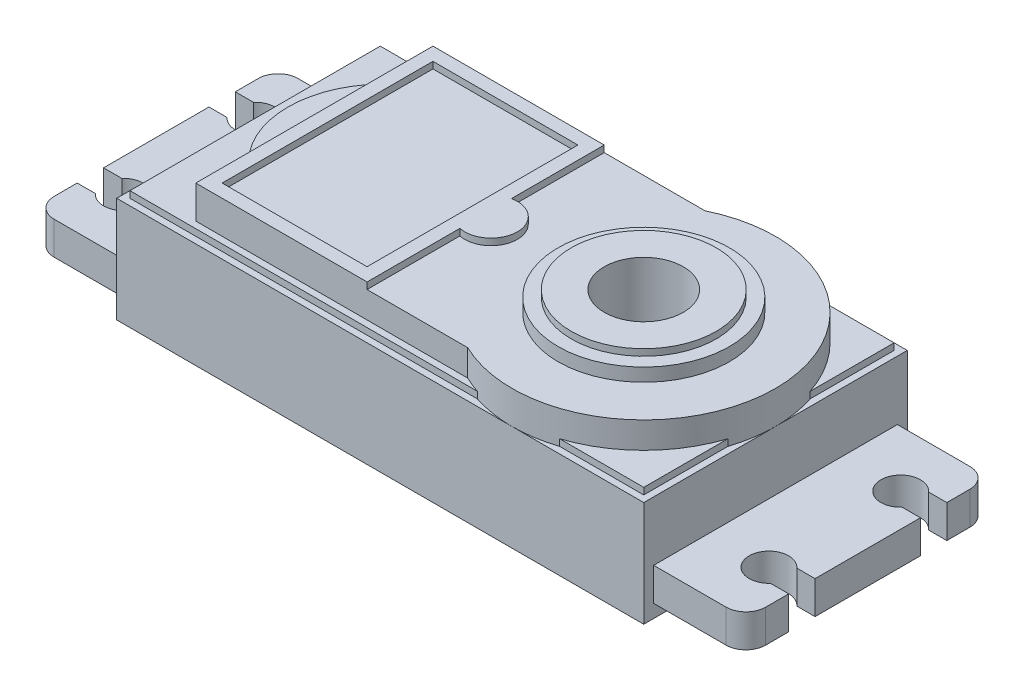
SolidWorks part; units mm, degrees
ref_plane "Piano frontale" through (0, 0, 0) normal (0, 0, 1) x (1, 0, 0)
ref_plane "Piano superiore" through (0, 0, 0) normal (0, 1, 0) x (1, 0, 0)
ref_plane "Piano destro" through (0, 0, 0) normal (1, 0, 0) x (0, 0, -1)
sketch "Schizzo2" plane through (0, 0, 0) normal (0, 1, 0) x (1, 0, 0)
  line L1 (20, -10) -> (-20, -10)
  line L2 (20, -10) -> (20, 10)
  line L3 (20, 10) -> (-20, 10)
  line L4 (-20, -10) -> (-20, 10)
  line L5 (20, -10) -> (-20, 10) construction
  line L6 (20, 10) -> (-20, -10) construction
  point P0 (0, 0)
  dimension "D1" = 20
  dimension "D2" = 40
extrude "Estrusione-Estrusione2" add sketch "Schizzo2" along normal blind 8
sketch "Schizzo3" plane through (0, 0, 0) normal (0, 1, 0) x (1, 0, 0)
  line L0 (-20, 10) -> (-20, -10) construction
  line L1 (16, -8) -> (-16, -8)
  line L2 (18, -6) -> (18, 6)
  line L3 (16, 8) -> (-16, 8)
  line L4 (-18, -6) -> (-18, 6)
  line L5 (16, -7.1111) -> (-16, 7.1111) construction
  line L6 (16, 7.1111) -> (-16, -7.1111) construction
  line L7 (20, 10) -> (-20, 10) construction
  line L8 (-16, 8) -> (-16, 6)
  line L9 (-16, 6) -> (-18, 6)
  line L10 (-18, -6) -> (-16, -6)
  line L11 (-16, -6) -> (-16, -8)
  line L12 (16, 8) -> (16, 6)
  line L13 (16, 6) -> (18, 6)
  line L14 (18, -6) -> (16, -6)
  line L15 (16, -6) -> (16, -8)
  point P0 (0, 0)
  dimension "D1" = 2
  dimension "D2" = 2
  dimension "D3" = 2
extrude "Taglio-Estrusione4" cut sketch "Schizzo3" along normal blind 6
hole_wizard "Foro per Vite M1-1" positions "Schizzo3D1" profile "Schizzo4" hole size "M1" standard "KS"
sketch3d "Schizzo3D1"
  line L0 (-20, 0, -10) -> (-20, 0, 10) construction
  line L1 (-20, 0, 10) -> (20, 0, 10) construction
  point P0 (-18, 0, 8)
  dimension "D1" = 2
  dimension "D2" = 2
sketch "Schizzo4" plane through (-18, 0, 8) normal (1, 0, 0) x (0, 0, -1)
  line L0 (0, 0) -> (0, 5.3906)
  line L1 (0, 5.3906) -> (0.65, 5)
  line L2 (0.65, 5) -> (0.65, 0.025)
  line L3 (0.65, 0.025) -> (0.675, 0)
  line L5 (0.675, 0) -> (0, 0)
  line L6 (-0.65, 0.025) -> (-0.675, 0) construction
  line L10 (0, 5.3906) -> (-0.65, 5) construction
  line L11 (0, -6.35) -> (0, 107.95) construction
  dimension "Hole Dia." = 1.3
  dimension "Hole Depth" = 5
  dimension "Near C'Sink Dia." = 1.35
  dimension "Near C'Sink Angle" = 90
  dimension "Drill Angle" = 118
mirror "Specchia1" about plane through (0, 0, 0) normal (1, 0, 0) of "Foro per Vite M1-1"
mirror "Specchia2" about plane through (0, 0, 0) normal (0, 0, 1) of "Specchia1", "Foro per Vite M1-1"
sketch "Schizzo5" plane through (0, 0, 0) normal (0, -1, 0) x (1, 0, 0)
  line L0 (-20, -10) -> (-20, 10) construction
  line L1 (19, -9) -> (-19, -9)
  line L2 (19, -9) -> (19, 9)
  line L3 (19, 9) -> (-19, 9)
  line L4 (-19, -9) -> (-19, 9)
  line L5 (19, -9) -> (-19, 9) construction
  line L6 (19, 9) -> (-19, -9) construction
  line L7 (-20, 10) -> (20, 10) construction
  point P0 (0, 0)
  dimension "D1" = 1
  dimension "D2" = 1
sketch "Schizzo7" plane through (0, 0, 0) normal (0, 0, 1) x (1, 0, 0)
  line L0 (19, 0) -> (-19, 0) construction
  line L1 (19, 0) -> (-19, 0) construction
  line L2 (-20, 8) -> (-20, 0) construction
  line L3 (-19.25, 0) -> (-18.75, 0)
  arc A0 (-18.75, 0) -> (-19.25, 0) centre (-19, 0) ccw
  dimension "D1" = 0.5
  dimension "D2" = 1
sweep "Taglia-Sweep3" cut profiles "Schizzo7" path "Schizzo5"
sketch "Schizzo9" plane through (0, 8, 0) normal (0, 1, 0) x (1, 0, 0)
  line L0 (-20, 10) -> (-20, -10) construction
  line L1 (-15, 9) -> (5.6411, 9)
  line L2 (-15, 9) -> (-15, 5)
  line L3 (-15, -9) -> (11.8461, -9)
  line L5 (-15, 9) -> (11.8461, -9) construction
  line L6 (-15, -9) -> (11.8461, 9) construction
  line L7 (-20, -10) -> (20, -10) construction
  line L8 (20, 10) -> (-20, 10) construction
  line L9 (20, -10) -> (20, 10) construction
  line L10 (-15, -5) -> (-15, -9)
  arc A0 (5.6411, -9) -> (5.6411, 9) centre (10, 0) ccw
  arc A1 (-15, -5) -> (-15, 5) centre (-9.75, 0) cw
  point P0 (-1.5769, 0)
  point P19 (-17, 0)
  dimension "D1" = 5
  dimension "D2" = 1
  dimension "D3" = 1
  dimension "D4" = 10
  dimension "D5" = 2
extrude "Estrusione-Estrusione4" add sketch "Schizzo9" along normal blind 2.5
sketch "Schizzo8" plane through (0, 8, 0) normal (0, 1, 0) x (1, 0, 0)
  line L0 (20, 10) -> (10, 10) construction
  line L1 (-19.5, -9.5) -> (19.5, -9.5)
  line L2 (-19.5, -9.5) -> (-19.5, 9.5)
  line L3 (-19.5, 9.5) -> (19.5, 9.5)
  line L4 (19.5, -9.5) -> (19.5, 9.5)
  line L5 (-19.5, -9.5) -> (19.5, 9.5) construction
  line L6 (-19.5, 9.5) -> (19.5, -9.5) construction
  line L7 (-20, 10) -> (-20, -10) construction
  point P0 (0, 0)
  dimension "D1" = 0.5
  dimension "D2" = 0.5
extrude "Estrusione-Estrusione3" add sketch "Schizzo8" along normal blind 0.5
sketch "Schizzo10" plane through (0, 10.5, 0) normal (0, 1, 0) x (1, 0, 0)
  line L0 (-15, -9) -> (5.6411, -9) construction
  line L1 (-15, 9) -> (-2, 9)
  line L2 (-15, 9) -> (-15, -9)
  line L3 (-15, -9) -> (-2, -9)
  line L4 (-2, 9) -> (-2, 1.9577)
  line L5 (-20, 10) -> (-20, -10) construction
  line L6 (-14, -8) -> (-3, -8)
  line L7 (-14, -8) -> (-14, 8)
  line L8 (-14, 8) -> (-3, 8)
  line L9 (-3, -8) -> (-3, 8)
  line L10 (-14, -8) -> (-3, 8) construction
  line L11 (-14, 8) -> (-3, -8) construction
  line L12 (-2, -1.9577) -> (-2, -9)
  arc A0 (-2, -1.9577) -> (-2, 1.9577) centre (-1.5909, 0) ccw
  point P7 (-8.5, 0)
  point P14 (0, 0)
  dimension "D6" = 4
  dimension "D7" = 18.4091
  dimension "D1" = 1
  dimension "D2" = 1
  dimension "D3" = 1
  dimension "D4" = 1
  dimension "D5" = 13
extrude "Estrusione-Estrusione5" add sketch "Schizzo10" along normal blind 0.5
sketch "Schizzo11" plane through (0, 10.5, 0) normal (0, 1, 0) x (1, 0, 0)
  circle A0 centre (10, 0) radius 6.5
  dimension "D1" = 13
extrude "Estrusione-Estrusione6" add sketch "Schizzo11" along normal blind 1
sketch "Schizzo12" plane through (0, 11.5, 0) normal (0, 1, 0) x (1, 0, 0)
  circle A0 centre (10, 0) radius 5.5
  dimension "D1" = 11
extrude "Estrusione-Estrusione7" add sketch "Schizzo12" along normal blind 0.5
sketch "Schizzo13" plane through (0, 12, 0) normal (0, 1, 0) x (1, 0, 0)
  circle A0 centre (10, 0) radius 3
  dimension "D1" = 6
extrude "Taglio-Estrusione5" cut sketch "Schizzo13" against normal through all
ref_plane "Piano1" through (0, 1, 0) normal (0, -1, 0) x (-1, 0, 0)
sketch "Schizzo15" plane through (0, 1, 0) normal (0, -1, 0) x (-1, 0, 0)
  line L0 (-20, -10) -> (-20, 10) construction
  line L2 (-25.5, 9.25) -> (-20, 9.25)
  line L3 (-27, 7.75) -> (-27, -7.75)
  line L4 (-25.5, -9.25) -> (-20, -9.25)
  line L5 (-20, 9.25) -> (-20, -9.25)
  line L6 (-27, 9.25) -> (-20, -9.25) construction
  line L7 (-27, -9.25) -> (-20, 9.25) construction
  arc A0 (-25.5, -9.25) -> (-27, -7.75) centre (-25.5, -7.75) cw
  arc A1 (-27, 7.75) -> (-25.5, 9.25) centre (-25.5, 7.75) cw
  circle A2 centre (-24.5, 5) radius 1.5
  circle A3 centre (-24.5, -5) radius 1.5
  point P0 (-23.5, 0)
  point P19 (0, 0)
  point P20 (0, 0)
  point P21 (0, 0)
  dimension "D3" = 1.5
  dimension "D4" = 3
  dimension "D1" = 18.5
  dimension "D2" = 7
  dimension "D5" = 10
  dimension "D6" = 2.5
  dimension "D7" = 5
extrude "Estrusione-Estrusione8" add sketch "Schizzo15" against normal blind 2.5
sketch "Schizzo17" plane through (0, 3.5, 0) normal (0, 1, 0) x (1, 0, 0)
  line L1 (30.9082, -5.9404) -> (24.8886, -5.9404)
  line L2 (30.9082, -5.9404) -> (30.9082, -4.9899)
  line L3 (30.9082, -4.9899) -> (24.8886, -4.9899)
  line L4 (24.8886, -5.9404) -> (24.8886, -4.9899)
  line L5 (30.9082, -5.9404) -> (24.8886, -4.9899) construction
  line L6 (30.9082, -4.9899) -> (24.8886, -5.9404) construction
  line L7 (34.3221, 4) -> (25.3835, 4)
  line L8 (34.3221, 4) -> (34.3221, 6)
  line L9 (34.3221, 6) -> (25.3835, 6)
  line L10 (25.3835, 4) -> (25.3835, 6)
  line L11 (34.3221, 4) -> (25.3835, 6) construction
  line L12 (34.3221, 6) -> (25.3835, 4) construction
  circle A0 centre (24.5, 5) radius 1.5 construction
  arc A1 (25.618, 4) -> (25.6727, 4.0647) centre (24.5, 5) ccw
  arc A2 (25.6727, 5.9353) -> (25.618, 6) centre (24.5, 5) ccw
  point P0 (27.8984, -5.4652)
  point P5 (29.8528, 5)
  point P10 (0, 0)
  circle M8 centre (24.5, 5) radius 1.5
  line M12 (27, -7.75) -> (27, 7.75)
  dimension "D1" = 2
  dimension "D2" = 8.9386
extrude "Taglio-Estrusione6" cut sketch "Schizzo17" against normal through all contours L8 L9 L7 M12 | L9 L7 M12 M8
mirror "Specchia3" about plane through (0, 0, 0) normal (0, 0, 1) of "Taglio-Estrusione6"
mirror "Specchia4" about plane through (0, 0, 0) normal (1, 0, 0) of "Specchia3", "Taglio-Estrusione6", "Estrusione-Estrusione8"
